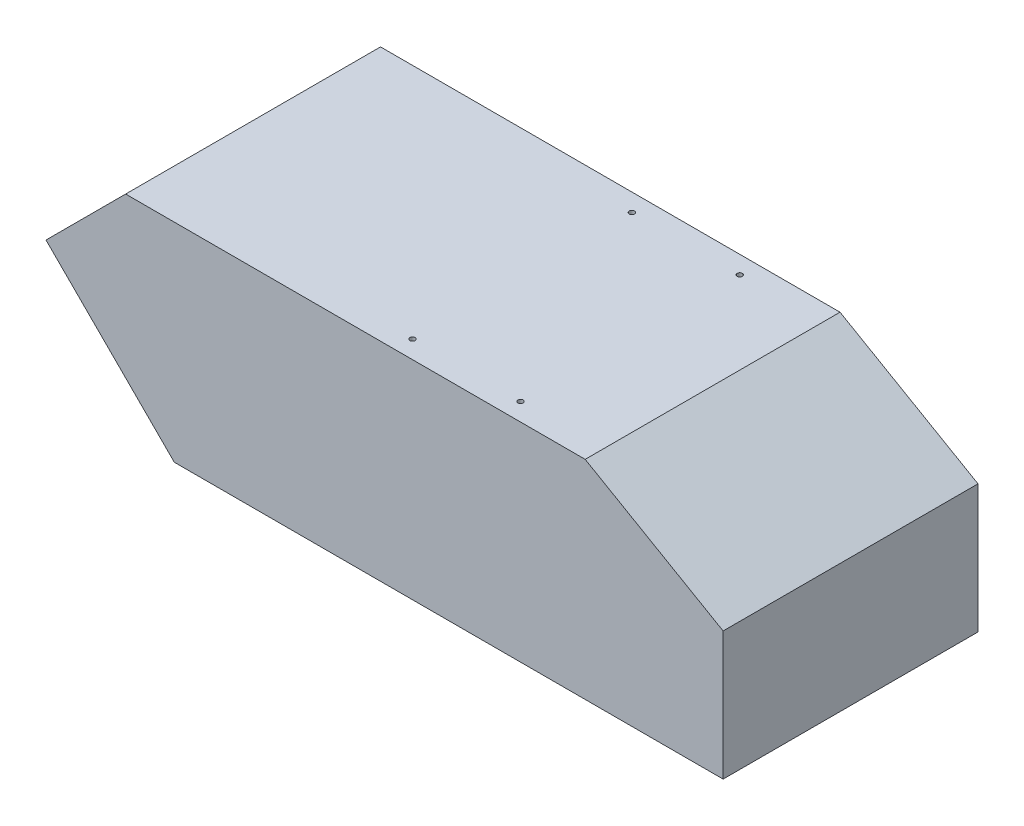
SolidWorks part; units mm, degrees
ref_plane "Front" through (0, 0, 0) normal (0, 0, 1) x (1, 0, 0)
ref_plane "Top" through (0, 0, 0) normal (0, 1, 0) x (1, 0, 0)
ref_plane "Right" through (0, 0, 0) normal (1, 0, 0) x (0, 0, -1)
sketch "Croquis3" plane through (0, 0, 0) normal (0, 0, 1) x (1, 0, 0)
  line L0 (-344.53, -161.11) -> (344.53, -161.11)
  line L2 (344.53, -161.11) -> (344.53, 0)
  line L3 (344.53, 0) -> (171.3249, 100)
  line L4 (171.3249, 100) -> (-405.64, 100)
  line L5 (-405.64, 100) -> (-505.64, 0)
  line L6 (-505.64, 0) -> (-344.53, -161.11)
  line L7 (0, -55) -> (0, 55) construction
  line L8 (55, 0) -> (-55, 0) construction
  point P11 (0, -161.11)
  dimension "D1" = 850.17
  dimension "D2" = 261.11
  dimension "D3" = 45
  dimension "D4" = 30
  dimension "D5" = 45
  dimension "D6" = 100
extrude "Saliente-Extruir2" add sketch "Croquis3" along normal mid plane 320
hole_wizard "Taladro de margen para M61" positions "Croquis6" profile "Croquis8" hole size "M6" standard "Ansi Metric"
sketch "Croquis6" plane through (0, 100, 0) normal (0, 1, 0) x (1, 0, 0)
  line L1 (-67.795, -137.645) -> (67.795, -137.645) construction
  line L2 (-67.795, -137.645) -> (-67.795, 137.645) construction
  line L3 (-67.795, 137.645) -> (67.795, 137.645) construction
  line L4 (67.795, -137.645) -> (67.795, 137.645) construction
  line L5 (-67.795, -137.645) -> (67.795, 137.645) construction
  line L6 (-67.795, 137.645) -> (67.795, -137.645) construction
  point P0 (-67.795, 137.645)
  point P4 (67.795, 137.645)
  point P17 (-67.795, -137.645)
  point P19 (67.795, -137.645)
  point P30 (0, 0)
  dimension "D1" = 275.29
  dimension "D2" = 135.59
sketch "Croquis8" plane through (-67.795, 100, -137.645) normal (1, 0, 0) x (0, 0, 1)
  line L0 (0, 0) -> (0, 23.9828)
  line L1 (0, 23.9828) -> (3.3, 22)
  line L2 (3.3, 22) -> (3.3, 0)
  line L5 (3.3, 0) -> (0, 0)
  line L10 (0, 23.9828) -> (-3.3, 22) construction
  line L11 (0, -6.35) -> (0, 107.95) construction
  dimension "Diámetro de taladro" = 6.6
  dimension "Profundidad de taladro" = 22
  dimension "Ángulo de perforador" = 118
